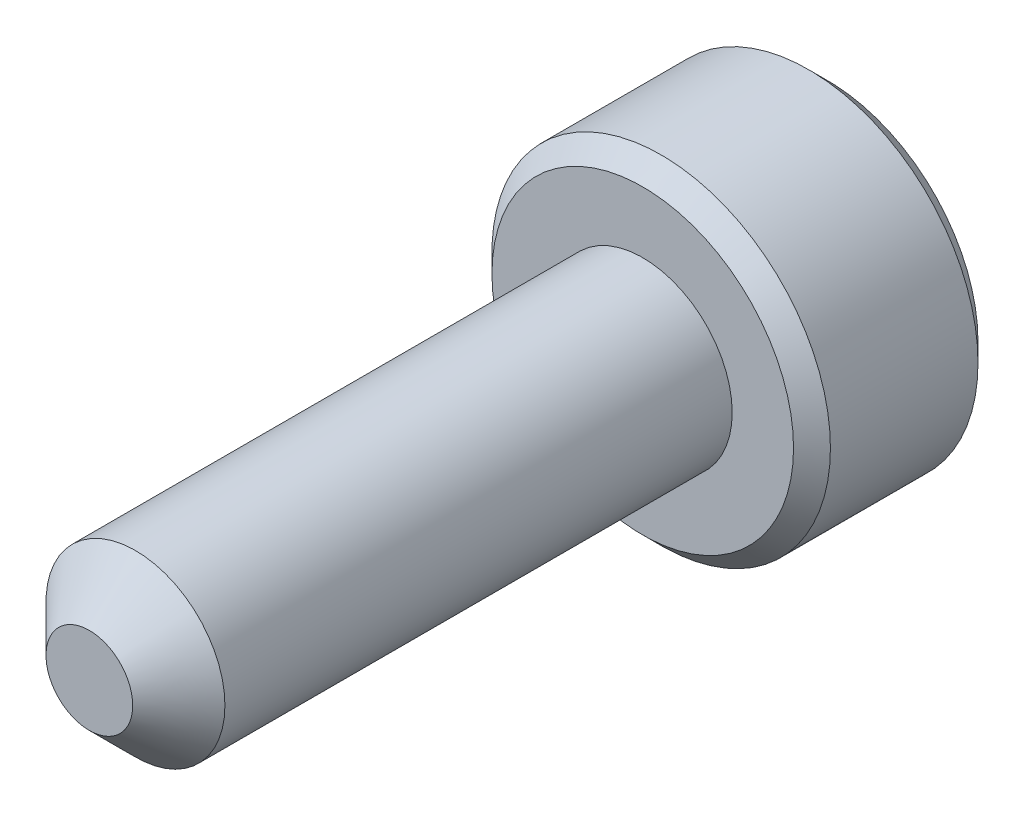
SolidWorks part; units mm, degrees
ref_plane "Front Plane" through (0, 0, 0) normal (0, 0, 1) x (1, 0, 0)
ref_plane "Top Plane" through (0, 0, 0) normal (0, 1, 0) x (1, 0, 0)
ref_plane "Right Plane" through (0, 0, 0) normal (1, 0, 0) x (0, 0, -1)
other "Configuration Table"
sketch "Sketch3" plane through (0, 0, 0) normal (0, 0, 1) x (1, 0, 0)
  circle A0 centre (0, 0) radius 1.835
  dimension "D1" = 3.67
extrude "Boss-Extrude1" add sketch "Sketch3" along normal blind 2
sketch "Sketch4" plane through (0, 0, 2) normal (0, 0, 1) x (1, 0, 0)
  circle A0 centre (0, 0) radius 0.97
extrude "Boss-Extrude2" add sketch "Sketch4" along normal blind 6
chamfer "Chamfer1" distance 0.5 angle 45 1 edges at (0.97, 0, 8)
sketch "Sketch5" plane through (0, 0, 0) normal (0, 0, -1) x (-1, 0, 0)
  line L1 (1.1453, 0) -> (0.5726, 0.9918)
  line L2 (0.5726, 0.9918) -> (-0.5726, 0.9918)
  line L3 (-0.5726, 0.9918) -> (-1.1453, 0)
  line L4 (-1.1453, 0) -> (-0.5726, -0.9918)
  line L5 (-0.5726, -0.9918) -> (0.5726, -0.9918)
  line L6 (0.5726, -0.9918) -> (1.1453, 0)
  circle A0 centre (0, 0) radius 0.9918 construction
extrude "Cut-Extrude1" cut sketch "Sketch5" against normal blind 1
chamfer "Chamfer2" distance 0.2 angle 45 2 edges at (1.835, 0, 2) (1.835, 0, 0)
